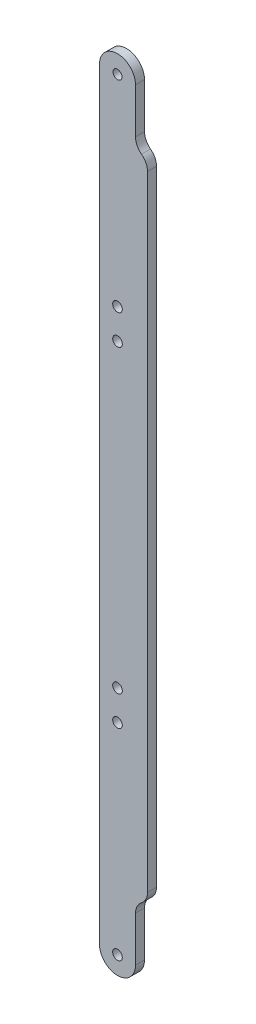
SolidWorks part; units mm, degrees
ref_plane "前视基准面" through (0, 0, 0) normal (0, 0, 1) x (1, 0, 0)
ref_plane "上视基准面" through (0, 0, 0) normal (0, 1, 0) x (1, 0, 0)
ref_plane "右视基准面" through (0, 0, 0) normal (1, 0, 0) x (0, 0, -1)
sketch "草图2" plane through (0, 0, 0) normal (0, 0, 1) x (1, 0, 0)
  line L1 (0, -43.1089) -> (-18, -43.1089)
  line L2 (0, -43.1089) -> (0, -133.1089)
  line L3 (0, -133.1089) -> (-18, -133.1089)
  line L4 (-18, -43.1089) -> (-18, -133.1089)
  circle A0 centre (-10, -125.1089) radius 1.6
  dimension "D1" = 18
  dimension "D2" = 8
  dimension "D3" = 3.2
  dimension "D4" = 82
  dimension "D5" = 8
extrude "凸台-拉伸1" add sketch "草图2" along normal blind 3
sketch "草图3" plane through (0, 0, 3) normal (0, 0, 1) x (1, 0, 0)
  line L0 (0, 1.8911) -> (-44.6895, 1.8911) construction
  line L1 (-18, 136.8911) -> (0, 136.8911)
  line L2 (-18, 46.8911) -> (-18, 136.8911)
  line L4 (0, -133.1089) -> (0, -43.1089)
  line L5 (0, -43.1089) -> (-18, -43.1089)
  line L6 (-18, -43.1089) -> (-18, -133.1089)
  line L7 (-18, -133.1089) -> (0, -133.1089)
  line L9 (0, -43.1089) -> (-18, -43.1089)
  line L12 (0, 136.8911) -> (0, 46.8911)
  line L15 (-18, 46.8911) -> (-18, -43.1089)
  line L16 (-18, -43.1089) -> (0, -43.1089)
  line L17 (0, 46.8911) -> (0, -43.1089)
  circle A1 centre (-10, 128.8911) radius 1.5
  line M11 (0, -43.1089) -> (-18, -43.1089)
  dimension "D3" = 8
  dimension "D4" = 10
  dimension "D5" = 127
  dimension "D2" = 45
  dimension "D1" = 0
extrude "凸台-拉伸2" add sketch "草图3" against normal blind 3 contours L0 L17 L12 L1 L2 L15 A1 | L17 L0 L15 M11
sketch "草图4" plane through (0, 0, 3) normal (0, 0, 1) x (1, 0, 0)
  circle A0 centre (-10, -58.1089) radius 1.6
  circle A1 centre (-10, -48.1089) radius 1.6
  circle A2 centre (-10, 51.8911) radius 1.6
  circle A3 centre (-10, 61.8911) radius 1.6
extrude "切除-拉伸1" cut sketch "草图4" against normal blind 3
sketch "草图5" plane through (0, 0, 3) normal (0, 0, 1) x (1, 0, 0)
  line L0 (-4, -125.1089) -> (-4, -110.1089)
  line L1 (0, -133.1089) -> (0, 136.8911) construction
  line L2 (-16, -125.1089) -> (-16, 128.8911)
  line L4 (0, 1.8911) -> (-11.675, 1.8911) construction
  line L5 (-16, 128.8911) -> (-16, -125.1089)
  line L6 (-4, 128.8911) -> (-4, 113.8911)
  line L7 (0, -102.1089) -> (0, -133.1089)
  line L8 (0, -133.1089) -> (-18, -133.1089)
  line L9 (-18, -133.1089) -> (-18, 136.8911)
  line L10 (-18, 136.8911) -> (0, 136.8911)
  line L11 (0, 136.8911) -> (0, 105.8911)
  circle A0 centre (-10, -125.1089) radius 6
  arc A1 (-4, -110.1089) -> (-2, -106.1089) centre (1, -110.1089) cw
  arc A2 (-2, -106.1089) -> (0, -102.1089) centre (-5, -102.1089) ccw
  arc A3 (-2, 109.8911) -> (0, 105.8911) centre (-5, 105.8911) cw
  arc A4 (-4, 113.8911) -> (-2, 109.8911) centre (1, 113.8911) ccw
  circle A5 centre (-10, 128.8911) radius 6
  line M7 (0, -133.1089) -> (0, 136.8911)
  line M8 (0, 136.8911) -> (-18, 136.8911)
  line M9 (-18, 136.8911) -> (-18, -133.1089)
  line M10 (-18, -133.1089) -> (0, -133.1089)
  dimension "D1" = 12
  dimension "D2" = 5
  dimension "D3" = 5
  dimension "D5" = 127
  dimension "D4" = 15
extrude "切除-拉伸2" cut sketch "草图5" against normal blind 3 and the other way through all contours L2 A5 L6 A4 A3 A2 A1 L0 A0 M7 M8 M9 M10
